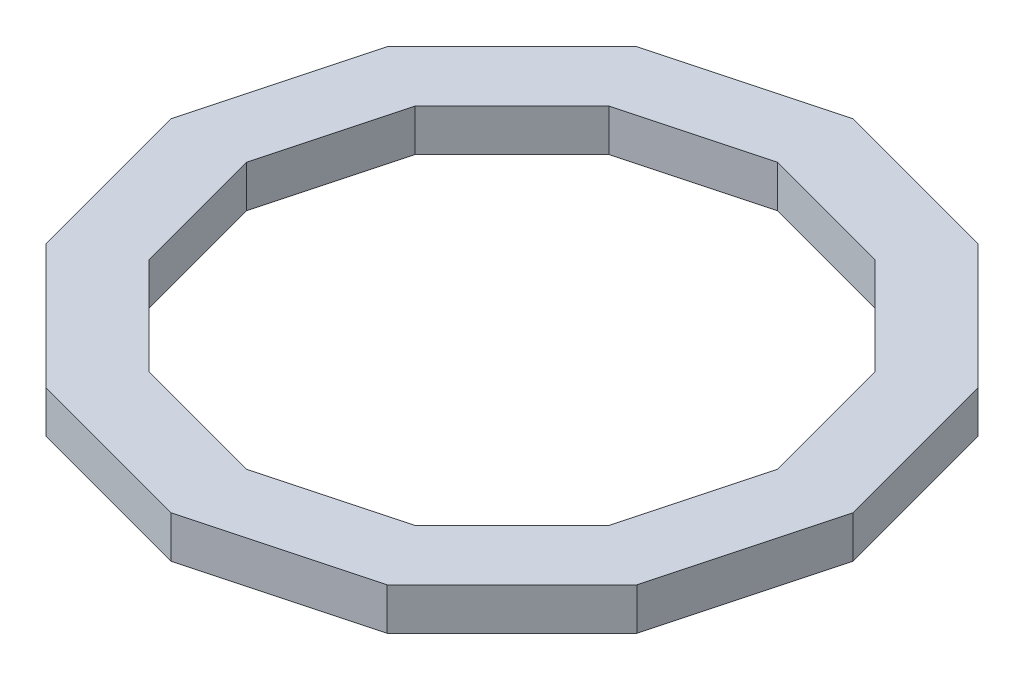
SolidWorks part; units mm, degrees
ref_plane "Front Plane" through (0, 0, 0) normal (0, 0, 1) x (1, 0, 0)
ref_plane "Top Plane" through (0, 0, 0) normal (0, 1, 0) x (1, 0, 0)
ref_plane "Right Plane" through (0, 0, 0) normal (1, 0, 0) x (0, 0, -1)
sketch "Sketch2" plane through (0, 0, 0) normal (0, 1, 0) x (1, 0, 0)
  line L0 (0, 0) -> (-120.3826, 0) construction
  line L1 (-154.5675, 0) -> (-133.8593, -77.2837)
  line L2 (-133.8593, -77.2837) -> (-77.2837, -133.8593)
  line L3 (-77.2837, -133.8593) -> (0, -154.5675)
  line L4 (0, -154.5675) -> (77.2837, -133.8593)
  line L5 (77.2837, -133.8593) -> (133.8593, -77.2837)
  line L6 (133.8593, -77.2837) -> (154.5675, 0)
  line L7 (154.5675, 0) -> (133.8593, 77.2837)
  line L8 (133.8593, 77.2837) -> (77.2837, 133.8593)
  line L9 (77.2837, 133.8593) -> (0, 154.5675)
  line L10 (0, 154.5675) -> (-77.2837, 133.8593)
  line L11 (-77.2837, 133.8593) -> (-133.8593, 77.2837)
  line L12 (-133.8593, 77.2837) -> (-154.5675, 0)
  line L13 (-120.3826, 0) -> (-104.2544, -60.1913)
  line L14 (-104.2544, -60.1913) -> (-60.1913, -104.2544)
  line L15 (-60.1913, -104.2544) -> (0, -120.3826)
  line L16 (0, -120.3826) -> (60.1913, -104.2544)
  line L17 (60.1913, -104.2544) -> (104.2544, -60.1913)
  line L18 (104.2544, -60.1913) -> (120.3826, 0)
  line L19 (120.3826, 0) -> (104.2544, 60.1913)
  line L20 (104.2544, 60.1913) -> (60.1913, 104.2544)
  line L21 (60.1913, 104.2544) -> (0, 120.3826)
  line L22 (0, 120.3826) -> (-60.1913, 104.2544)
  line L23 (-60.1913, 104.2544) -> (-104.2544, 60.1913)
  line L24 (-104.2544, 60.1913) -> (-120.3826, 0)
  line L25 (-154.5675, 0) -> (-120.3826, 0) construction
  circle A0 centre (0, 0) radius 149.3007 construction
  circle A1 centre (0, 0) radius 116.2807 construction
  dimension "D1" = 80.01
  dimension "D2" = 33.02
extrude "Boss-Extrude2" add sketch "Sketch2" along normal blind 19.05
